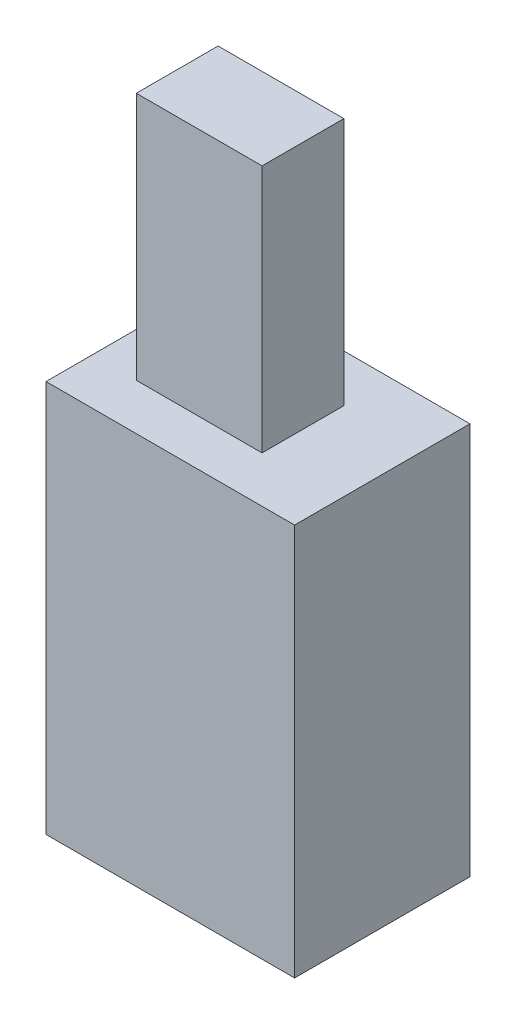
SolidWorks part; units mm, degrees
ref_plane "Front Plane" through (0, 0, 0) normal (0, 0, 1) x (1, 0, 0)
ref_plane "Top Plane" through (0, 0, 0) normal (0, 1, 0) x (1, 0, 0)
ref_plane "Right Plane" through (0, 0, 0) normal (1, 0, 0) x (0, 0, -1)
sketch "Sketch2" plane through (0, 0, 0) normal (1, 0, 0) x (0, 0, -1)
  line L1 (-23.0545, 13.9356) -> (5.1687, 13.9356)
  line L2 (-23.0545, 13.9356) -> (-23.0545, -49.1827)
  line L3 (-23.0545, -49.1827) -> (5.1687, -49.1827)
  line L4 (5.1687, 13.9356) -> (5.1687, -49.1827)
extrude "Boss-Extrude1" add sketch "Sketch2" along normal blind 40
sketch "Sketch3" plane through (0, 13.9356, 0) normal (0, 1, 0) x (1, 0, 0)
  line L1 (7.0867, -2.4504) -> (27.3271, -2.4504)
  line L2 (7.0867, -2.4504) -> (7.0867, -15.6159)
  line L3 (7.0867, -15.6159) -> (27.3271, -15.6159)
  line L4 (27.3271, -2.4504) -> (27.3271, -15.6159)
extrude "Boss-Extrude2" add sketch "Sketch3" along normal blind 40
sketch "Sketch4" plane through (0, -49.1827, 0) normal (0, -1, 0) x (-1, 0, 0)
  line L1 (-3.2651, -13.9214) -> (-1.4938, -13.9214)
  line L2 (-3.2651, -13.9214) -> (-3.2651, 3.5077)
  line L3 (-3.2651, 3.5077) -> (-1.4938, 3.5077)
  line L4 (-1.4938, -13.9214) -> (-1.4938, 3.5077)
extrude "Boss-Extrude3" add sketch "Sketch4" along normal blind 5
